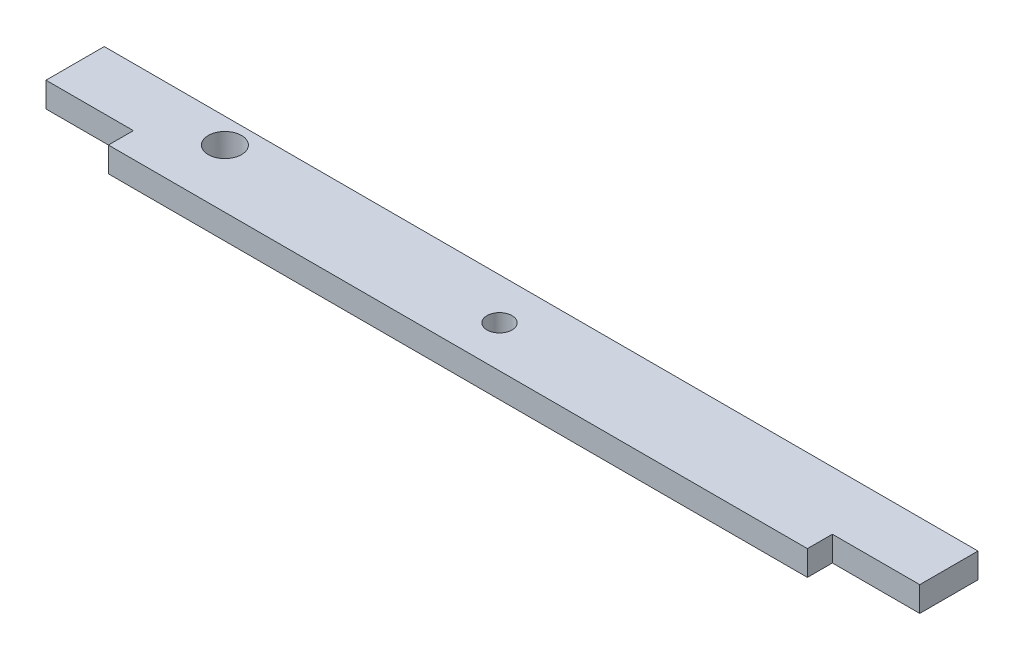
SolidWorks part; units mm, degrees
ref_plane "Front" through (0, 0, 0) normal (0, 0, 1) x (1, 0, 0)
ref_plane "Top" through (0, 0, 0) normal (0, 1, 0) x (1, 0, 0)
ref_plane "Right" through (0, 0, 0) normal (1, 0, 0) x (0, 0, -1)
sketch "Sketch1" plane through (0, 0, 0) normal (0, 1, 0) x (1, 0, 0)
  line L1 (-52.5, 5) -> (52.5, 5)
  line L2 (-52.5, 5) -> (-52.5, -5)
  line L3 (-52.5, -5) -> (52.5, -5)
  line L4 (52.5, 5) -> (52.5, -5)
  line L5 (-52.5, 5) -> (52.5, -5) construction
  line L6 (-52.5, -5) -> (52.5, 5) construction
  circle A0 centre (0, 0) radius 1.5
  point P0 (0, 0)
  dimension "D3" = 3
  dimension "D1" = 105
  dimension "D2" = 10
extrude "Boss-Extrude1" add sketch "Sketch1" along normal blind 3
sketch "Sketch2" plane through (0, 3, 0) normal (0, 1, 0) x (1, 0, 0)
  line L0 (-52.5, -5) -> (-42, -5)
  line L1 (-52.5, -5) -> (52.5, -5) construction
  line L2 (-42, -5) -> (-42, -2)
  line L3 (-42, -2) -> (-52.5, -2)
  line L6 (-52.5, -2) -> (-52.5, -5)
  dimension "D1" = 10.5
  dimension "D2" = 3
extrude "Cut-Extrude1" cut sketch "Sketch2" against normal through all
mirror "Mirror2" about plane through (0, 0, 0) normal (1, 0, 0) of "Cut-Extrude1"
sketch "Sketch3" plane through (0, 0, 0) normal (0, -1, 0) x (1, 0, 0)
  line L0 (0, 0) -> (-35, 0)
  line L1 (-35, 0) -> (-35, -2)
  circle A1 centre (-35, -2) radius 2
  dimension "D2" = 4
  dimension "D3" = 2
  dimension "D1" = 35
extrude "Cut-Extrude3" cut sketch "Sketch3" against normal blind 10
